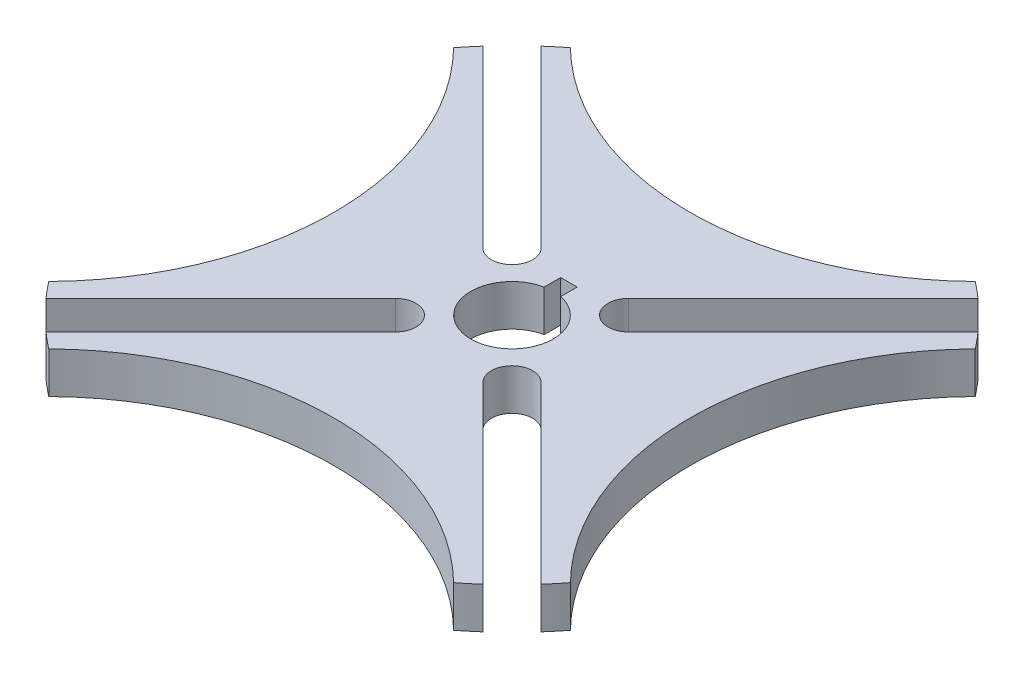
SolidWorks part; units mm, degrees
ref_plane "前视基准面" through (0, 0, 0) normal (0, 0, 1) x (1, 0, 0)
ref_plane "上视基准面" through (0, 0, 0) normal (0, 1, 0) x (1, 0, 0)
ref_plane "右视基准面" through (0, 0, 0) normal (1, 0, 0) x (0, 0, -1)
sketch "草图1" plane through (0, 0, 0) normal (0, 1, 0) x (1, 0, 0)
  line L0 (-140.9891, 0) -> (181.7796, 0) construction
  line L1 (0, 0) -> (0, -4.5365) construction
  line L2 (0, 10) -> (0, -10) construction
  line L3 (0, 113.1371) -> (0, -118.3615) construction
  line L4 (-56.5685, 56.5685) -> (56.5685, -56.5685) construction
  line L5 (7.0711, -7.0711) -> (7.2826, -7.2826) construction
  line L6 (56.5685, 56.5685) -> (-56.5685, -56.5685) construction
  line L7 (-7.0711, -7.0711) -> (-7.2826, -7.2826) construction
  line L8 (7.0711, 7.0711) -> (7.2826, 7.2826) construction
  line L9 (-98.9949, 98.9949) -> (-14.1421, 14.1421) construction
  line L10 (59.9935, 52.9224) -> (17.6777, 10.6066)
  line L11 (-52.9224, 59.9935) -> (-10.6066, 17.6777)
  line L12 (-59.9935, 52.9224) -> (-17.6777, 10.6066)
  line L13 (52.9224, 59.9935) -> (10.6066, 17.6777)
  line L14 (52.9224, -59.9935) -> (10.6066, -17.6777)
  line L15 (59.9935, -52.9224) -> (17.6777, -10.6066)
  line L16 (-59.9935, -52.9224) -> (-17.6777, -10.6066)
  line L17 (-52.9224, -59.9935) -> (-10.6066, -17.6777)
  line L18 (0, 0) -> (0, 113.1371) construction
  line L19 (-2, 9.798) -> (-2, 13.798)
  line L20 (-2, 13.798) -> (2, 13.798)
  line L21 (2, 9.798) -> (2, 13.798)
  arc A0 (-59.9935, 52.9224) -> (-63.1977, 49.0516) centre (0, 0) ccw
  arc A1 (-2, 9.798) -> (2, 9.798) centre (0, 0) ccw
  arc A2 (10.6066, 17.6777) -> (17.6777, 10.6066) centre (14.1421, 14.1421) ccw
  arc A3 (-17.6777, 10.6066) -> (-10.6066, 17.6777) centre (-14.1421, 14.1421) ccw
  arc A4 (17.6777, -10.6066) -> (10.6066, -17.6777) centre (14.1421, -14.1421) ccw
  arc A5 (-10.6066, -17.6777) -> (-17.6777, -10.6066) centre (-14.1421, -14.1421) ccw
  arc A6 (52.9224, 59.9935) -> (49.0516, 63.1977) centre (0, 0) ccw
  arc A7 (59.9935, -52.9224) -> (63.1977, -49.0516) centre (0, 0) ccw
  arc A8 (-52.9224, -59.9935) -> (-49.0516, -63.1977) centre (0, 0) ccw
  arc A9 (-49.0516, 63.1977) -> (49.0516, 63.1977) centre (0, 113.1371) ccw
  arc A10 (-49.0516, 63.1977) -> (-52.9224, 59.9935) centre (0, 0) ccw
  arc A11 (63.1977, 49.0516) -> (63.1977, -49.0516) centre (113.1371, 0) ccw
  arc A12 (49.0516, -63.1977) -> (-49.0516, -63.1977) centre (0, -113.1371) ccw
  arc A13 (-63.1977, -49.0516) -> (-63.1977, 49.0516) centre (-113.1371, 0) ccw
  arc A14 (-63.1977, -49.0516) -> (-59.9935, -52.9224) centre (0, 0) ccw
  arc A15 (49.0516, -63.1977) -> (52.9224, -59.9935) centre (0, 0) ccw
  arc A16 (63.1977, 49.0516) -> (59.9935, 52.9224) centre (0, 0) ccw
  point P13 (0, 6.8215)
  point P19 (-35.3553, 35.3553)
  point P24 (0, 86.8325)
  point P28 (-56.5685, 56.5685)
  point P35 (0, 0)
  point P49 (0, 0)
  point P54 (0, 0)
  point P62 (0, 0)
  point P65 (0, 13.798)
  dimension "D1" = 160
  dimension "D2" = 45
  dimension "D3" = 4
  dimension "D4" = 113.1371
  dimension "D5" = 4
  dimension "D8" = 10
  dimension "D6" = 4
  dimension "D7" = 4
extrude "凸台-拉伸1" add sketch "草图1" along normal blind 10
